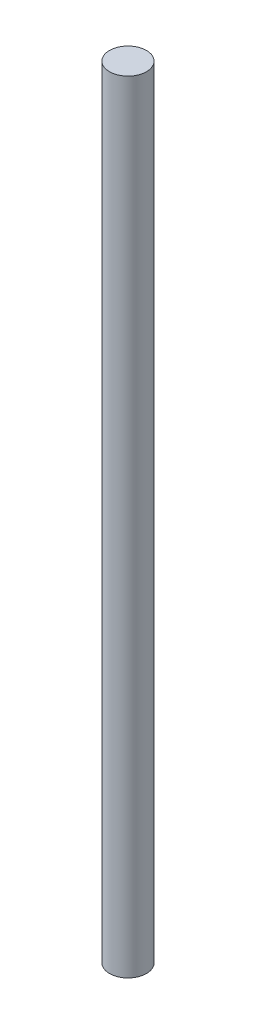
SolidWorks part; units mm, degrees
ref_plane "Front Plane" through (0, 0, 0) normal (0, 0, 1) x (1, 0, 0)
ref_plane "Top Plane" through (0, 0, 0) normal (0, 1, 0) x (1, 0, 0)
ref_plane "Right Plane" through (0, 0, 0) normal (1, 0, 0) x (0, 0, -1)
sketch "Sketch1" plane through (0, 0, 0) normal (0, 1, 0) x (1, 0, 0)
  circle A0 centre (0, 0) radius 2.3633
  dimension "D1" = 4.7265
extrude "Boss-Extrude1" add sketch "Sketch1" along normal blind 100
